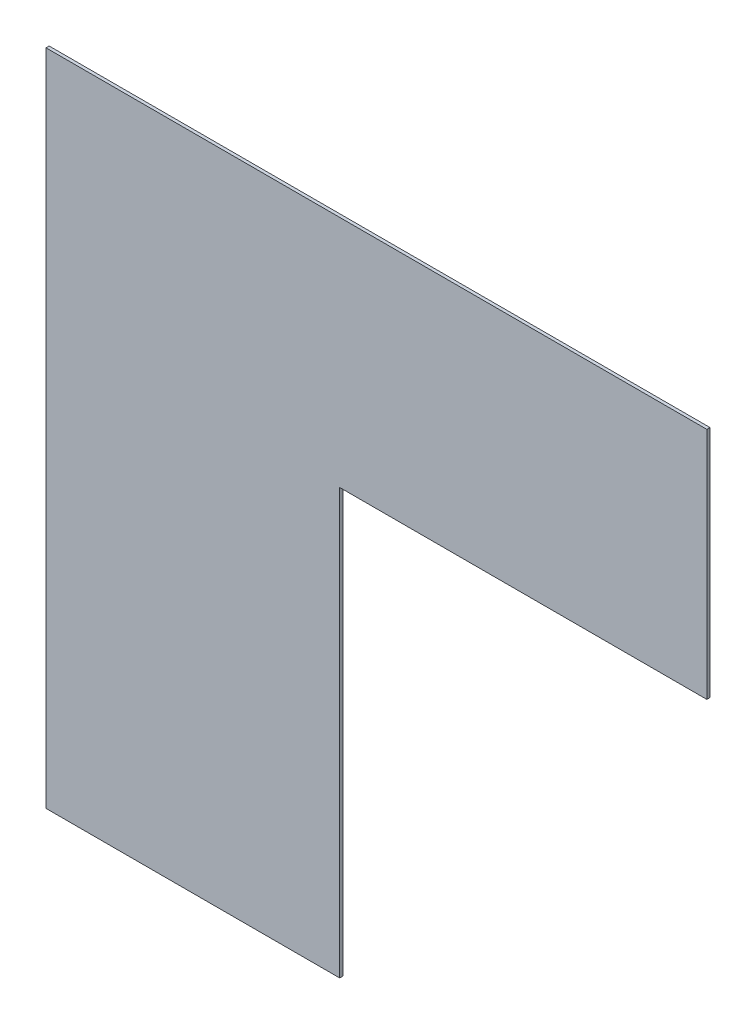
SolidWorks part; units mm, degrees
ref_plane "Plan de face" through (0, 0, 0) normal (0, 0, 1) x (1, 0, 0)
ref_plane "Plan de dessus" through (0, 0, 0) normal (0, 1, 0) x (1, 0, 0)
ref_plane "Plan de droite" through (0, 0, 0) normal (1, 0, 0) x (0, 0, -1)
sketch "Esquisse1" plane through (0, 0, 0) normal (0, 0, 1) x (1, 0, 0)
  line L0 (350, 628) -> (-280, 628)
  line L1 (0, 0) -> (-280, 0)
  line L2 (0, 0) -> (0, 405)
  line L3 (0, 405) -> (350, 405)
  line L4 (350, 628) -> (350, 405)
  line L5 (0, 528.9179) -> (0, -528.9179) construction
  line L6 (-494.0155, 0) -> (494.0155, 0) construction
  line L7 (-280, 628) -> (-280, 0)
  point P0 (0, 0)
  dimension "D1" = 630
  dimension "D2" = 628
  dimension "D3" = 223
  dimension "D4" = 350
extrude "Boss.-Extru.1" add sketch "Esquisse1" along normal blind 3
